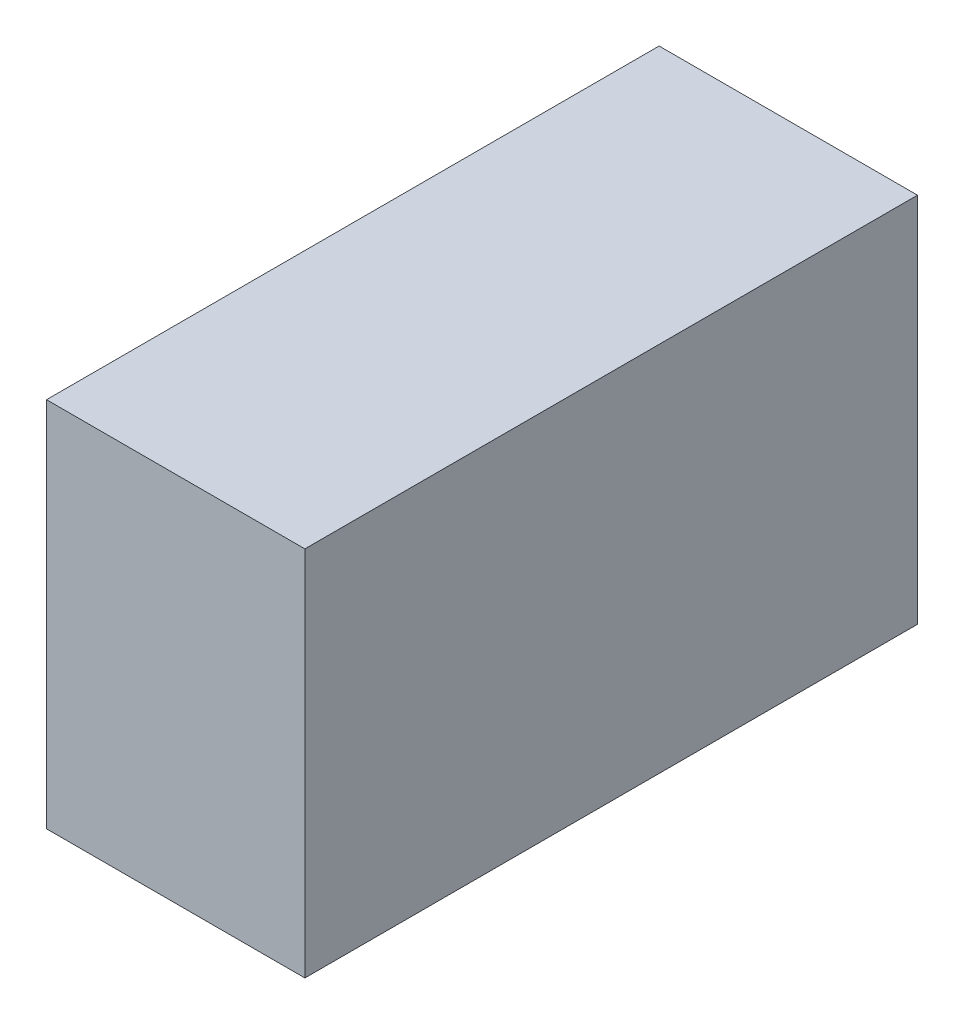
SolidWorks part; units mm, degrees
ref_plane "Front Plane" through (0, 0, 0) normal (0, 0, 1) x (1, 0, 0)
ref_plane "Top Plane" through (0, 0, 0) normal (0, 1, 0) x (1, 0, 0)
ref_plane "Right Plane" through (0, 0, 0) normal (1, 0, 0) x (0, 0, -1)
sketch "Sketch1" plane through (0, 0, 0) normal (0, 1, 0) x (1, 0, 0)
  line L1 (0, 0) -> (134.874, 0)
  line L2 (0, 0) -> (0, 319.786)
  line L3 (0, 319.786) -> (134.874, 319.786)
  line L4 (134.874, 0) -> (134.874, 319.786)
  dimension "D1" = 134.874
  dimension "D2" = 319.786
extrude "Boss-Extrude1" add sketch "Sketch1" along normal blind 194
